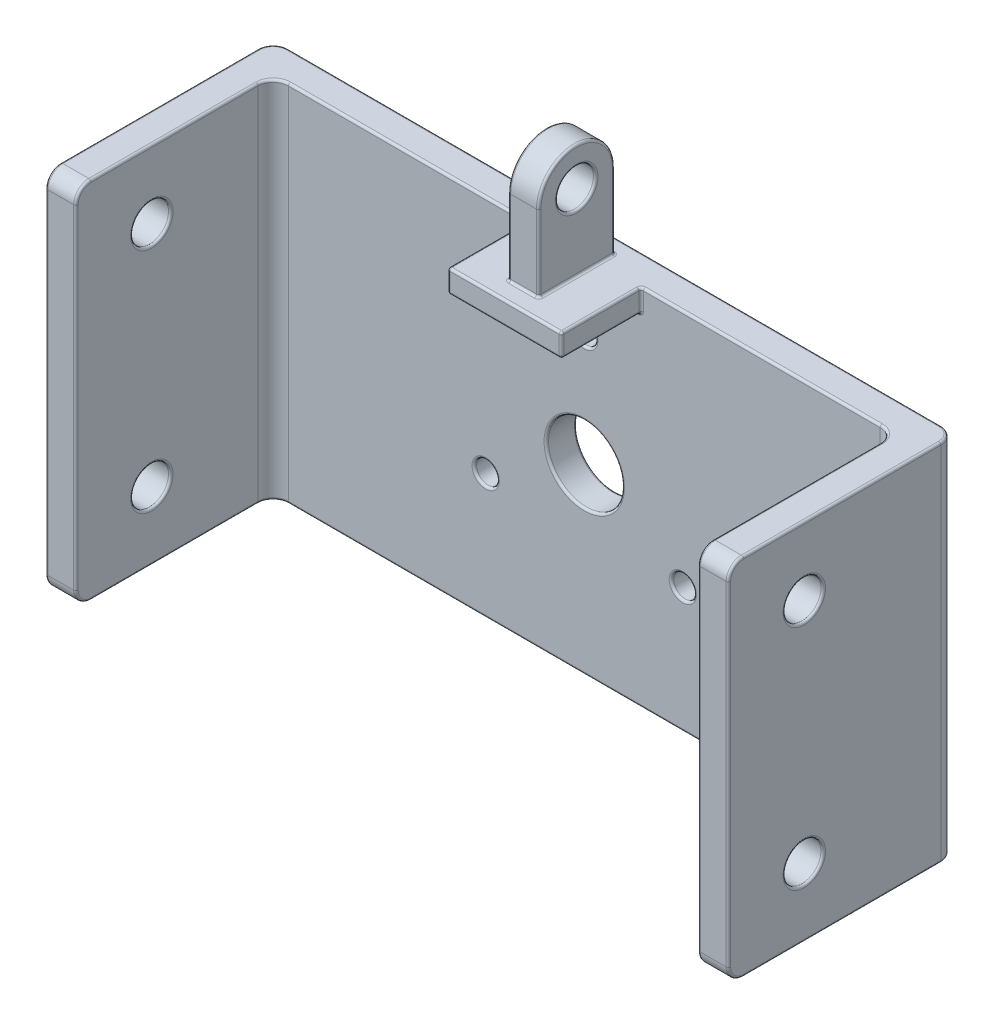
SolidWorks part; units mm, degrees
ref_plane "Front Plane" through (0, 0, 0) normal (0, 0, 1) x (1, 0, 0)
ref_plane "Top Plane" through (0, 0, 0) normal (0, 1, 0) x (1, 0, 0)
ref_plane "Right Plane" through (0, 0, 0) normal (1, 0, 0) x (0, 0, -1)
sketch "Sketch1" plane through (0, 0, 0) normal (0, 1, 0) x (1, 0, 0)
  line L0 (-22.5, -15) -> (-22.5, 0)
  line L1 (-22.5, 0) -> (22.5, 0)
  line L2 (22.5, 0) -> (22.5, -15)
  line L3 (-20.5, -15) -> (-20.5, -2)
  line L4 (-20.5, -2) -> (20.5, -2)
  line L5 (20.5, -2) -> (20.5, -15)
  line L6 (22.5, -15) -> (20.5, -15)
  line L7 (-20.5, -15) -> (-22.5, -15)
  point P5 (0, 0)
  dimension "D1" = 45
  dimension "D2" = 15
  dimension "D3" = 2
extrude "Boss-Extrude1" add sketch "Sketch1" along normal blind 24
sketch "Sketch2" plane through (0, 0, 0) normal (1, 0, 0) x (0, 0, -1)
  line L0 (0, 12) -> (-18.7294, 12) construction
  line L1 (0, 24) -> (0, 0) construction
  line L2 (-15, 24) -> (-15, 0) construction
  circle A0 centre (-10, 19.5) radius 1.25
  circle A1 centre (-10, 4.5) radius 1.25
  point P8 (0, 0)
  dimension "D2" = 2.5
  dimension "D1" = 15
  dimension "D3" = 5
extrude "Cut-Extrude1" cut sketch "Sketch2" against normal up to surface and the other way up to surface up to face at (-22.5, 12, 7.5) other way up to face at (22.5, 12, 7.5)
sketch "Sketch3" plane through (0, 0, 0) normal (0, 0, 1) x (1, 0, 0)
  line L0 (0, 0) -> (0, 24) construction
  line L1 (-20.5, 24) -> (20.5, 24) construction
  circle A0 centre (0, 12) radius 2.5
  circle A1 centre (0, 12) radius 10 construction
  circle A2 centre (0, 19.5) radius 0.75
  circle A3 centre (6.4952, 8.25) radius 0.75
  circle A4 centre (-6.4952, 8.25) radius 0.75
  dimension "D1" = 20
  dimension "D2" = 5
  dimension "D3" = 1.5
  dimension "D4" = 7.5
  dimension "D5" = 3
extrude "Cut-Extrude2" cut sketch "Sketch3" along normal up to surface (2 mm away) up to face at (0, 12, 2)
fillet "Fillet1" radius 1 4 edges at (21.5, 0, 15) (21.5, 24, 15) (-21.5, 0, 15) (-21.5, 24, 15)
fillet "Fillet2" radius 1 4 edges at (22.5, 12, 0) (-22.5, 12, 0) (-20.5, 12, 2) (20.5, 12, 2)
sketch "Sketch4" plane through (0, 24, 0) normal (0, 1, 0) x (1, 0, 0)
  line L0 (21.5, 0) -> (-21.5, 0) construction
  line L1 (-3.75, -2) -> (3.75, -2)
  line L2 (-3.75, -2) -> (-3.75, -7.25)
  line L3 (-3.75, -7.25) -> (3.75, -7.25)
  line L4 (3.75, -2) -> (3.75, -7.25)
  line L5 (-3.75, -2) -> (3.75, -7.25) construction
  line L6 (-3.75, -7.25) -> (3.75, -2) construction
  line L7 (-19.5, -2) -> (19.5, -2) construction
  point P0 (0, -4.625)
  point P5 (0, 0)
  point P8 (0, 0)
  point P11 (0, -2)
  point P12 (0, -2)
  dimension "D1" = 5.25
  dimension "D2" = 7.5
extrude "Boss-Extrude2" add sketch "Sketch4" against normal blind 1.5
sketch "Sketch5" plane through (0, 0, 0) normal (1, 0, 0) x (0, 0, -1)
  line L0 (-14, 24) -> (-1, 24) construction
  line L1 (-1, 29) -> (-1, 24)
  line L2 (-6, 29) -> (-6, 24)
  line L3 (-6, 24) -> (-1, 24)
  circle A0 centre (-3.5, 29) radius 1.25
  arc A1 (-1, 29) -> (-6, 29) centre (-3.5, 29) ccw
  circle A2 centre (-3.5, 29) radius 2.5 construction
  dimension "D1" = 2.5
  dimension "D2" = 5
  dimension "D3" = 1.25
extrude "Boss-Extrude3" add sketch "Sketch5" along normal blind 1 and the other way blind 1
fillet "Fillet3" radius 0.15 72 edges at (1, 29, 2.25) (1, 31.5, 3.5) (1, 26.5, 6) (1, 24, 3.5) (1, 26.5, 1) (-1, 29, 2.25) (-1, 31.5, 3.5) (-1, 26.5, 6) (-1, 24, 3.5) (-1, 26.5, 1) (0, 24, 6) (0, 24, 1) (3.75, 24, 4.625) (3.75, 22.5, 4.625) (-3.75, 24, 4.625) (-3.75, 22.5, 4.625) (0, 24, 7.25) (0, 22.5, 7.25) (0, 22.5, 2) (3.75, 23.25, 2) (-3.75, 23.25, 2) (-3.75, 23.25, 7.25) (3.75, 23.25, 7.25) (-5.7452, 8.25, 0) (-7.2452, 8.25, 2) (7.2452, 8.25, 0) (5.7452, 8.25, 2) (0.75, 19.5, 0) (-0.75, 19.5, 2) (2.5, 12, 0) (-2.5, 12, 2) (22.5, 4.5, 11.25) (-22.5, 4.5, 8.75) (22.5, 19.5, 11.25) (-22.5, 19.5, 8.75) (20.5, 4.5, 8.75) (-20.5, 4.5, 11.25) (20.5, 19.5, 8.75) (-20.5, 19.5, 11.25) (-20.5, 0, 8.5) (0, 0, 2) (20.5, 0, 8.5) (22.5, 0, 7.5) (0, 0, 0) (-22.5, 0, 7.5) (-20.5, 24, 8.5) (11.625, 24, 2) (-11.625, 24, 2) (20.5, 24, 8.5) (22.5, 24, 7.5) (0, 24, 0) (-22.5, 24, 7.5) (-22.5, 12, 15) (20.5, 12, 15) (-20.5, 12, 15) (22.5, 23.7071, 14.7071) (22.5, 0.2929, 14.7071) (20.5, 23.7071, 14.7071) (20.5, 0.2929, 14.7071) (-20.5, 23.7071, 14.7071) (-20.5, 0.2929, 14.7071) (-22.5, 23.7071, 14.7071) (-22.5, 0.2929, 14.7071) (-22.2071, 0, 0.2929) (22.2071, 0, 0.2929) (-22.2071, 24, 0.2929) (22.2071, 24, 0.2929) (-20.2071, 0, 2.2929) (-20.2071, 24, 2.2929) (20.2071, 0, 2.2929) (20.2071, 24, 2.2929) (22.5, 12, 15)
